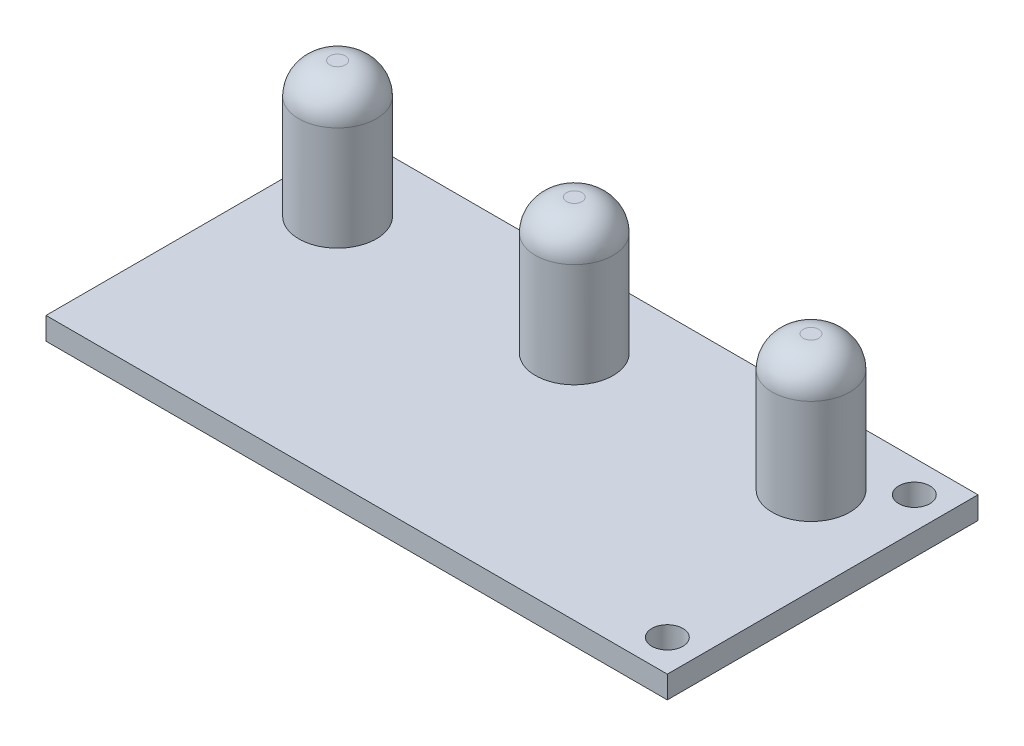
SolidWorks part; units mm, degrees
ref_plane "Front" through (0, 0, 0) normal (0, 0, 1) x (1, 0, 0)
ref_plane "Top" through (0, 0, 0) normal (0, 1, 0) x (1, 0, 0)
ref_plane "Right" through (0, 0, 0) normal (1, 0, 0) x (0, 0, -1)
sketch "Sketch1" plane through (0, 0, 0) normal (0, 1, 0) x (1, 0, 0)
  line L1 (-20, -10) -> (20, -10)
  line L2 (-20, -10) -> (-20, 10)
  line L3 (-20, 10) -> (20, 10)
  line L4 (20, -10) -> (20, 10)
  line L5 (-20, -10) -> (20, 10) construction
  line L6 (-20, 10) -> (20, -10) construction
  point P0 (0, 0)
  dimension "D1" = 40
  dimension "D2" = 20
extrude "Boss-Extrude1" add sketch "Sketch1" along normal blind 1.44
sketch "Sketch2" plane through (0, 1.44, 0) normal (0, 1, 0) x (1, 0, 0)
  line L0 (-16.13, 4.9) -> (-0.89, 4.9) construction
  line L1 (-0.89, 4.9) -> (14.35, 4.9) construction
  line L2 (20, -10) -> (20, 10) construction
  line L3 (20, 10) -> (-20, 10) construction
  circle A0 centre (14.35, 4.9) radius 2.5
  circle A1 centre (-0.89, 4.9) radius 2.5
  circle A2 centre (-16.13, 4.9) radius 2.5
  dimension "D3" = 5
  dimension "D1" = 15.24
  dimension "D2" = 5.65
  dimension "D4" = 5.1
extrude "Boss-Extrude2" add sketch "Sketch2" along normal blind 8.7
fillet "Fillet1" radius 2 3 edges at (14.35, 10.14, -2.4) (-0.89, 10.14, -2.4) (-16.13, 10.14, -2.4)
sketch "Sketch3" plane through (0, 1.44, 0) normal (0, 1, 0) x (1, 0, 0)
  line L0 (20, 10) -> (-20, 10) construction
  line L1 (20, -10) -> (20, 10) construction
  line L2 (-20, -10) -> (20, -10) construction
  circle A0 centre (17.95, 7.95) radius 1
  circle A1 centre (17.95, -7.95) radius 1
  dimension "D1" = 2.05
  dimension "D3" = 2
  dimension "D2" = 2.05
  dimension "D4" = 2.05
extrude "Cut-Extrude1" cut sketch "Sketch3" against normal through all
